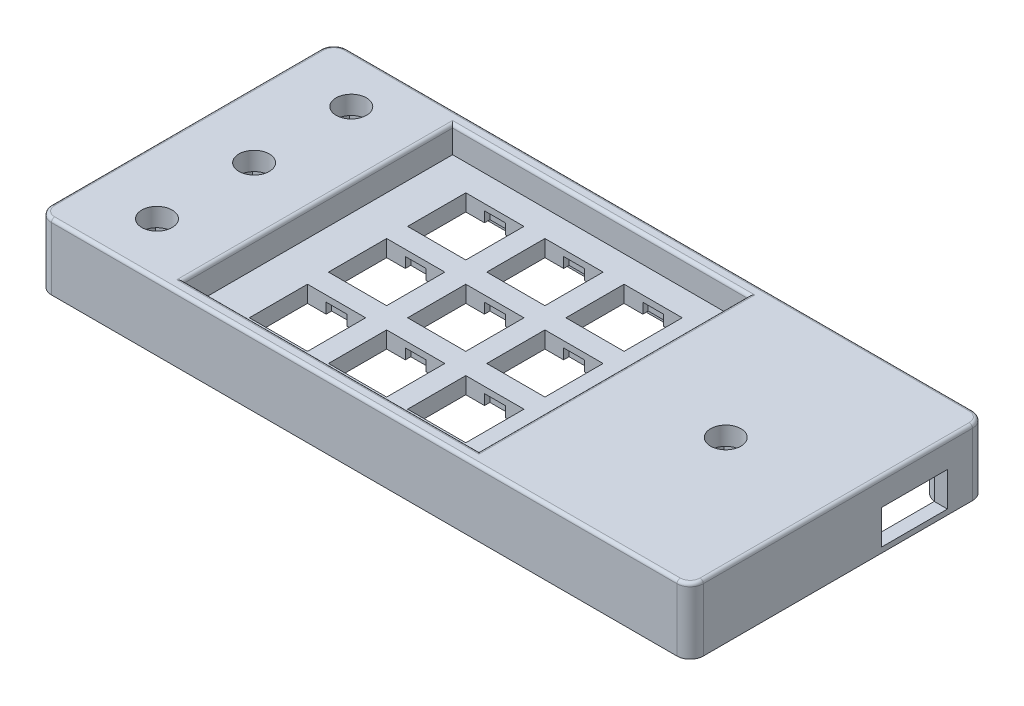
SolidWorks part; units mm, degrees
ref_plane "Front Plane" through (0, 0, 0) normal (0, 0, 1) x (1, 0, 0)
ref_plane "Top Plane" through (0, 0, 0) normal (0, 1, 0) x (1, 0, 0)
ref_plane "Right Plane" through (0, 0, 0) normal (1, 0, 0) x (0, 0, -1)
sketch "Sketch1" plane through (0, 0, 0) normal (0, 1, 0) x (1, 0, 0)
  line L1 (0, 0) -> (71.1479, 0)
  line L2 (0, 0) -> (0, 71.1479)
  line L3 (0, 71.1479) -> (71.1479, 71.1479)
  line L4 (71.1479, 0) -> (71.1479, 71.1479)
  dimension "D1" = 71.1479
  dimension "D2" = 71.1479
extrude "Boss-Extrude1" add sketch "Sketch1" along normal blind 4
sketch "Sketch2" plane through (0, 4, 0) normal (0, 1, 0) x (1, 0, 0)
  line L0 (9.525, 23.525) -> (23.525, 23.525)
  line L1 (9.525, 23.525) -> (9.525, 9.525)
  line L2 (9.525, 9.525) -> (23.525, 9.525)
  line L3 (23.525, 23.525) -> (23.525, 9.525)
  line L4 (0, 71.1479) -> (0, 0) construction
  line L5 (0, 0) -> (71.1479, 0) construction
  dimension "D1" = 9.525
  dimension "D2" = 9.525
  dimension "D3" = 14
extrude "Cut-Extrude1" cut sketch "Sketch2" against normal through all
sketch "Sketch3" plane through (0, 4, 0) normal (0, 1, 0) x (1, 0, 0)
  line L0 (14.0255, 23.525) -> (19.0245, 23.525)
  line L1 (14.0255, 23.525) -> (14.0255, 24.8321)
  line L2 (14.0255, 24.8321) -> (19.0245, 24.8321)
  line L3 (19.0245, 23.525) -> (19.0245, 24.8321)
  line L4 (9.525, 16.525) -> (23.525, 16.525) construction
  line L5 (9.525, 23.525) -> (9.525, 9.525) construction
  line L6 (23.525, 9.525) -> (23.525, 23.525) construction
  line L7 (23.525, 23.525) -> (9.525, 23.525) construction
  line L8 (14.0255, 9.525) -> (14.0255, 8.2179)
  line L9 (14.0255, 8.2179) -> (19.0245, 8.2179)
  line L10 (19.0245, 9.525) -> (19.0245, 8.2179)
  line L11 (14.0255, 9.525) -> (19.0245, 9.525)
  point P13 (16.525, 23.525)
  point P14 (16.525, 16.525)
  dimension "D1" = 4.999
  dimension "D2" = 1.3071
extrude "Cut-Extrude2" cut sketch "Sketch3" along normal blind 2.5001 from surface at -4 starting at face at (16.525, 0, -16.525)
pattern_linear "LPattern1" count 3 spacing 19.049 along (1, 0, 0) count 3 spacing 19.049 along (0, 0, -1) of "Cut-Extrude2", "Cut-Extrude1"
sketch "Sketch4" plane through (0, 0, 0) normal (0, 1, 0) x (1, 0, 0)
  line L0 (71.1479, 71.1479) -> (0, 71.1479) construction
  line L1 (0, 0) -> (-31.75, 0)
  line L2 (0, 0) -> (0, 71.1479)
  line L3 (0, 71.1479) -> (-31.75, 71.1479)
  line L4 (-31.75, 0) -> (-31.75, 71.1479)
  dimension "D1" = 31.75
extrude "Boss-Extrude2" add sketch "Sketch4" along normal blind 12.7 from offset 2.35 offset against normal yes
sketch "Sketch5" plane through (0, 10.35, 0) normal (0, 1, 0) x (1, 0, 0)
  line L0 (-31.75, 12.7) -> (0, 12.7) construction
  line L1 (-31.75, 71.1479) -> (-31.75, 0) construction
  line L2 (0, 0) -> (0, 71.1479) construction
  line L4 (-31.75, 0) -> (0, 0) construction
  circle A0 centre (-15.875, 12.7) radius 3.6576
  dimension "D1" = 7.3152
  dimension "D2" = 12.7
extrude "Cut-Extrude3" cut sketch "Sketch5" against normal blind 4.445
sketch "Sketch6" plane through (0, 10.35, 0) normal (0, 1, 0) x (1, 0, 0)
  line L0 (-22.86, 19.304) -> (-8.89, 19.304)
  line L1 (-22.86, 19.304) -> (-22.86, 6.096)
  line L2 (-22.86, 6.096) -> (-8.89, 6.096)
  line L3 (-8.89, 19.304) -> (-8.89, 6.096)
  line L4 (-31.75, 12.7) -> (0, 12.7) construction
  point P6 (-22.86, 12.7)
  point P10 (-15.875, 6.096)
  dimension "D1" = 13.97
  dimension "D2" = 13.208
extrude "Cut-Extrude4" cut sketch "Sketch6" along normal up to surface (8.255 mm away) from surface at -12.7 up to face at (-15.875, 5.905, -9.0424) starting at face at (-15.875, -2.35, -35.574)
sketch "Sketch7" plane through (0, -2.35, 0) normal (0, -1, 0) x (1, 0, 0)
  line L0 (-22.86, -9.2075) -> (-24.13, -9.2075)
  line L1 (-22.86, -9.2075) -> (-22.86, -16.1925)
  line L2 (-22.86, -16.1925) -> (-24.13, -16.1925)
  line L3 (-24.13, -9.2075) -> (-24.13, -16.1925)
  line L4 (-22.86, -6.096) -> (-22.86, -19.304) construction
  line L5 (-15.875, -6.096) -> (-15.875, -19.304) construction
  line L6 (-8.89, -6.096) -> (-22.86, -6.096) construction
  line L7 (-22.86, -19.304) -> (-8.89, -19.304) construction
  line L8 (-8.89, -9.2075) -> (-8.89, -16.1925)
  line L9 (-8.89, -16.1925) -> (-7.62, -16.1925)
  line L10 (-7.62, -9.2075) -> (-7.62, -16.1925)
  line L11 (-8.89, -9.2075) -> (-7.62, -9.2075)
  point P7 (-22.86, -12.7)
  point P8 (-22.86, -12.7)
  dimension "D1" = 6.985
  dimension "D2" = 1.27
extrude "Cut-Extrude5" cut sketch "Sketch7" against normal blind 3.175
pattern_linear "LPattern6" count 3 spacing 23.382 along (0, 0, -1) of "Cut-Extrude3", "Cut-Extrude4", "Cut-Extrude5"
sketch "Sketch9" plane through (0, 0, 0) normal (0, 1, 0) x (1, 0, 0)
  line L0 (71.1479, 0) -> (71.1479, 71.1479) construction
  line L1 (71.1479, 0) -> (125.144, 0)
  line L2 (71.1479, 0) -> (71.1479, 71.1479)
  line L3 (71.1479, 71.1479) -> (125.144, 71.1479)
  line L4 (125.144, 0) -> (125.144, 71.1479)
  line L5 (71.1479, 71.1479) -> (0, 71.1479) construction
  line L6 (71.1479, 35.574) -> (125.144, 35.574) construction
  line L7 (0, 0) -> (71.1479, 0) construction
  circle A0 centre (98.146, 35.574) radius 22.225 construction
  dimension "D1" = 44.45
extrude "Boss-Extrude3" add sketch "Sketch9" along normal up to surface (12.7 mm away) from surface at -2.35 up to face at (-15.875, 10.35, -55.8063) starting at face at (-15.875, -2.35, -59.4639)
sketch "Sketch10" plane through (0, 10.35, 0) normal (0, 1, 0) x (1, 0, 0)
  line L3 (71.1479, 35.574) -> (125.144, 35.574) construction
  line L5 (71.1479, 0) -> (71.1479, 71.1479) construction
  line L6 (125.144, 0) -> (125.144, 71.1479) construction
  circle A0 centre (98.146, 35.574) radius 3.6576
  dimension "D1" = 7.3152
extrude "Cut-Extrude6" cut sketch "Sketch10" against normal blind 4.445
sketch "Sketch11" plane through (0, 5.905, 0) normal (0, 1, 0) x (1, 0, 0)
  line L0 (91.161, 42.178) -> (105.131, 42.178)
  line L1 (91.161, 42.178) -> (91.161, 28.97)
  line L2 (91.161, 28.97) -> (105.131, 28.97)
  line L3 (105.131, 42.178) -> (105.131, 28.97)
  line L5 (71.1479, 35.574) -> (125.144, 35.574) construction
  point P6 (91.161, 35.574)
  point P12 (98.146, 35.574)
  point P13 (98.146, 28.97)
  dimension "D1" = 13.97
  dimension "D2" = 13.208
extrude "Cut-Extrude7" cut sketch "Sketch11" along normal up to surface (8.255 mm away) from surface at -8.255 up to face at (98.146, 5.905, -31.9164) starting at face at (98.146, -2.35, -35.574)
sketch "Sketch14" plane through (0, -2.35, 0) normal (0, -1, 0) x (1, 0, 0)
  line L0 (91.161, -32.0815) -> (89.891, -32.0815)
  line L1 (91.161, -32.0815) -> (91.161, -39.0665)
  line L2 (91.161, -39.0665) -> (89.891, -39.0665)
  line L3 (89.891, -32.0815) -> (89.891, -39.0665)
  line L5 (98.146, -28.97) -> (98.146, -42.178) construction
  line L8 (105.131, -32.0815) -> (105.131, -39.0665)
  line L9 (105.131, -39.0665) -> (106.401, -39.0665)
  line L10 (106.401, -32.0815) -> (106.401, -39.0665)
  line L11 (105.131, -32.0815) -> (106.401, -32.0815)
  line L13 (91.161, -42.178) -> (105.131, -42.178) construction
  line L14 (105.131, -28.97) -> (91.161, -28.97) construction
  line L15 (91.161, -28.97) -> (91.161, -42.178) construction
  point P8 (91.161, -35.574)
  point P11 (98.146, -42.178)
  point P14 (98.146, -28.97)
  point P21 (91.161, -35.574)
  dimension "D1" = 6.985
  dimension "D2" = 1.27
extrude "Cut-Extrude10" cut sketch "Sketch14" against normal blind 3.175
sketch "Sketch15" plane through (0, 4, 0) normal (0, 1, 0) x (1, 0, 0)
  line L0 (71.1479, 71.1479) -> (71.1479, 0) construction
  line L1 (0, 71.1479) -> (71.1479, 71.1479)
  line L2 (0, 71.1479) -> (0, 67.9729)
  line L3 (0, 67.9729) -> (71.1479, 67.9729)
  line L4 (71.1479, 71.1479) -> (71.1479, 67.9729)
  line L6 (0, 0) -> (71.1479, 0)
  line L7 (0, 0) -> (0, 3.175)
  line L8 (0, 3.175) -> (71.1479, 3.175)
  line L9 (71.1479, 0) -> (71.1479, 3.175)
  dimension "D1" = 3.175
extrude "Boss-Extrude4" add sketch "Sketch15" along normal up to surface (6.35 mm away) up to face at (-15.875, 10.35, -55.8063)
sketch "Sketch18" plane through (0, -2.35, 0) normal (0, -1, 0) x (1, 0, 0)
  line L0 (-28.575, -67.9729) -> (-28.575, -3.175)
  line L1 (-31.75, -71.1479) -> (125.144, -71.1479)
  line L2 (-31.75, -71.1479) -> (-31.75, 0)
  line L3 (-31.75, 0) -> (125.144, 0)
  line L4 (125.144, -71.1479) -> (125.144, 0)
  line L5 (-28.575, -3.175) -> (121.969, -3.175)
  line L6 (121.969, -67.9729) -> (121.969, -3.175)
  line L7 (-28.575, -67.9729) -> (121.969, -67.9729)
  dimension "D1" = 3.175
extrude "Boss-Extrude9" add sketch "Sketch18" against normal up to body from offset 3.175
fillet "Fillet1" radius 3.175 8 edges at (-31.75, 2.4125, -71.1479) (125.144, 2.4125, -71.1479) (125.144, 2.4125, 0) (-31.75, 2.4125, 0) (121.969, -3.9375, -67.9729) (-28.575, -3.9375, -67.9729) (-28.575, -3.9375, -3.175) (121.969, -3.9375, -3.175)
fillet "Fillet2" radius 0.7937 12 edges at (124.2141, 10.35, -0.9299) (46.697, 10.35, 0) (-30.8201, 10.35, -0.9299) (-31.75, 10.35, -35.574) (-30.8201, 10.35, -70.218) (46.697, 10.35, -71.1479) (124.2141, 10.35, -70.218) (35.574, 10.35, -67.9729) (0, 10.35, -35.574) (35.574, 10.35, -3.175) (71.1479, 10.35, -35.574) (125.144, 10.35, -35.574)
sketch "Sketch19" plane through (0, -2.35, 0) normal (0, -1, 0) x (1, 0, 0)
  line L0 (105.131, -42.178) -> (91.161, -42.178) construction
  line L1 (88.621, -45.099) -> (107.671, -45.099)
  line L2 (88.621, -45.099) -> (88.621, -26.049)
  line L3 (88.621, -26.049) -> (107.671, -26.049)
  line L4 (71.1479, -67.9729) -> (118.794, -67.9729)
  line L6 (71.1479, -67.9729) -> (118.794, -67.9729)
  line L7 (71.1479, -3.175) -> (71.1479, -67.9729)
  line L11 (71.1479, -3.175) -> (71.1479, -67.9729)
  line L12 (107.671, -45.099) -> (107.671, -26.049)
  line L13 (91.161, -39.0665) -> (91.161, -32.0815) construction
  line L19 (121.969, -64.7979) -> (121.969, -6.35)
  line L21 (121.969, -64.7979) -> (121.969, -6.35)
  line L22 (118.794, -3.175) -> (71.1479, -3.175)
  line L23 (118.794, -3.175) -> (71.1479, -3.175)
  arc A2 (118.794, -67.9729) -> (121.969, -64.7979) centre (118.794, -64.7979) ccw
  arc A6 (118.794, -67.9729) -> (121.969, -64.7979) centre (118.794, -64.7979) ccw
  arc A8 (121.969, -6.35) -> (118.794, -3.175) centre (118.794, -6.35) ccw
  arc A9 (121.969, -6.35) -> (118.794, -3.175) centre (118.794, -6.35) ccw
  point P14 (98.146, -42.178)
  point P15 (98.146, -45.099)
  point P18 (91.161, -35.574)
  point P19 (88.621, -35.574)
  dimension "D2" = 19.05
  dimension "D1" = 0
extrude "Cut-Extrude11" cut sketch "Sketch19" against normal up to surface (2.35 mm away) up to face at (35.574, 0, -16.525)
sketch "Sketch20" plane through (0, 0, 0) normal (0, -1, 0) x (1, 0, 0)
  line L0 (71.1479, -3.175) -> (71.1479, -67.9729) construction
  line L1 (71.1479, -3.175) -> (71.1479, -67.9729) construction
  line L3 (-25.4, -67.9729) -> (118.794, -67.9729) construction
  line L4 (121.969, -64.7979) -> (121.969, -6.35) construction
  line L5 (118.794, -3.175) -> (-25.4, -3.175) construction
  line L7 (72.7354, -67.9729) -> (118.794, -67.9729)
  line L8 (121.969, -64.7979) -> (121.969, -6.35)
  line L9 (118.794, -3.175) -> (72.7354, -3.175)
  line L10 (72.7354, -3.175) -> (72.7354, -67.9729)
  line L11 (88.621, -45.099) -> (107.671, -45.099) construction
  line L12 (107.671, -45.099) -> (107.671, -26.049) construction
  line L13 (107.671, -26.049) -> (88.621, -26.049) construction
  line L14 (88.621, -26.049) -> (88.621, -45.099) construction
  line L15 (88.621, -45.099) -> (107.671, -45.099)
  line L16 (107.671, -45.099) -> (107.671, -26.049)
  line L17 (107.671, -26.049) -> (88.621, -26.049)
  line L18 (88.621, -26.049) -> (88.621, -45.099)
  arc A2 (118.794, -67.9729) -> (121.969, -64.7979) centre (118.794, -64.7979) ccw construction
  arc A3 (121.969, -6.35) -> (118.794, -3.175) centre (118.794, -6.35) ccw construction
  arc A6 (118.794, -67.9729) -> (121.969, -64.7979) centre (118.794, -64.7979) ccw
  arc A7 (121.969, -6.35) -> (118.794, -3.175) centre (118.794, -6.35) ccw
  dimension "D1" = 3.175
extrude "Cut-Extrude13" cut sketch "Sketch20" against normal offset from surface (7.175 mm away) 3.175 up to face at (35.574, 10.35, -35.574)
sketch "Sketch21" plane through (0, -5.525, 0) normal (0, -1, 0) x (1, 0, 0)
  line L0 (121.969, 0) -> (-28.575, 0) construction
  line L1 (-31.75, -3.175) -> (-31.75, -67.9729) construction
  line L2 (-28.575, -71.1479) -> (121.969, -71.1479) construction
  line L3 (0, -3.175) -> (0, -67.9729) construction
  line L4 (72.7354, -3.175) -> (72.7354, -67.9729) construction
  line L5 (125.144, -67.9729) -> (125.144, -3.175) construction
  circle A0 centre (-27.7812, -3.9688) radius 3.9688
  circle A1 centre (-27.7812, -67.1792) radius 3.9688
  circle A2 centre (121.1752, -67.1792) radius 3.9687
  circle A3 centre (121.1752, -3.9688) radius 3.9687
  circle A4 centre (0, -3.9688) radius 3.9688
  circle A5 centre (72.7354, -67.1792) radius 3.9688
  dimension "D1" = 7.9375
extrude "Boss-Extrude10" add sketch "Sketch21" against normal up to body
sketch "Sketch22" plane through (0, -5.525, 0) normal (0, -1, 0) x (1, 0, 0)
  circle A0 centre (-27.7812, -3.9688) radius 2.54
  circle A1 centre (0, -3.9688) radius 2.54
  circle A2 centre (72.7354, -67.1792) radius 2.54
  circle A3 centre (-27.7812, -67.1792) radius 2.54
  circle A4 centre (121.1752, -67.1792) radius 2.54
  circle A5 centre (121.1752, -3.9688) radius 2.54
  dimension "D1" = 5.08
extrude "Cut-Extrude14" cut sketch "Sketch22" against normal blind 8.001
sketch "Sketch24" plane through (0, 7.175, 0) normal (0, -1, 0) x (1, 0, 0)
  line L0 (121.969, -63.2906) -> (121.969, -7.8573) construction
  line L1 (86.409, -45.099) -> (121.969, -45.099) construction
  line L2 (86.409, -45.099) -> (86.409, -62.879) construction
  line L3 (86.409, -62.879) -> (121.969, -62.879) construction
  line L4 (121.969, -45.099) -> (121.969, -62.879) construction
  line L5 (88.621, -45.099) -> (107.671, -45.099) construction
  line L7 (118.794, -50.814) -> (121.969, -50.814)
  line L8 (118.794, -50.814) -> (118.794, -57.164)
  line L9 (118.794, -57.164) -> (121.969, -57.164)
  line L10 (121.969, -50.814) -> (121.969, -57.164)
  point P13 (121.969, -53.989)
  point P14 (121.969, -53.989)
  dimension "D1" = 17.78
  dimension "D2" = 35.56
  dimension "D3" = 3.175
  dimension "D4" = 6.35
extrude "Boss-Extrude11" add sketch "Sketch24" along normal blind 3.175
sketch "Sketch25" plane through (0, 7.175, 0) normal (0, -1, 0) x (1, 0, 0)
  line L0 (118.794, -50.814) -> (118.794, -57.164) construction
  line L1 (88.6315, -50.814) -> (94.9815, -50.814)
  line L2 (88.6315, -50.814) -> (88.6315, -57.164)
  line L3 (88.6315, -57.164) -> (94.9815, -57.164)
  line L4 (94.9815, -50.814) -> (94.9815, -57.164)
  line L5 (121.969, -45.099) -> (121.969, -62.879) construction
  point P6 (118.794, -53.989)
  point P7 (94.9815, -53.989)
  dimension "D1" = 6.35
  dimension "D2" = 26.9875
extrude "Boss-Extrude12" add sketch "Sketch25" along normal up to surface (3.175 mm away) up to face at (120.3815, 4, -53.989)
sketch "Sketch27" plane through (0, 7.175, 0) normal (0, -1, 0) x (1, 0, 0)
  line L0 (86.409, -62.879) -> (121.969, -62.879) construction
  line L1 (104.496, -62.879) -> (107.671, -62.879)
  line L2 (104.496, -62.879) -> (104.496, -67.9729)
  line L3 (104.496, -67.9729) -> (107.671, -67.9729)
  line L4 (107.671, -62.879) -> (107.671, -67.9729)
  line L5 (76.624, -67.9729) -> (117.2867, -67.9729) construction
  line L6 (107.671, -45.099) -> (107.671, -26.049) construction
  dimension "D1" = 3.175
extrude "Boss-Extrude13" add sketch "Sketch27" along normal blind 8.1915
sketch "Sketch26" plane through (0, 4, 0) normal (0, -1, 0) x (1, 0, 0)
  line L1 (104.496, -46.6865) -> (107.671, -46.6865)
  line L2 (104.496, -46.6865) -> (104.496, -45.099)
  line L3 (104.496, -45.099) -> (107.671, -45.099)
  line L4 (107.671, -46.6865) -> (107.671, -45.099)
  line L5 (107.671, -45.099) -> (107.671, -26.049) construction
  line L6 (86.409, -45.099) -> (121.969, -45.099) construction
  line L8 (104.496, -62.879) -> (107.671, -62.879)
  line L9 (104.496, -62.879) -> (104.496, -61.2915)
  line L10 (104.496, -61.2915) -> (107.671, -61.2915)
  line L11 (107.671, -62.879) -> (107.671, -61.2915)
  dimension "D1" = 3.175
  dimension "D2" = 1.5875
extrude "Boss-Extrude14" add sketch "Sketch26" along normal blind 1.5875 from offset 1.7145
sketch "Sketch28" plane through (121.969, 0, 0) normal (-1, 0, 0) x (0, 0, 1)
  line L0 (-57.164, 4) -> (-50.814, 4) construction
  line L1 (-61.9265, 4) -> (-46.0515, 4)
  line L2 (-61.9265, 4) -> (-61.9265, -4.255)
  line L3 (-61.9265, -4.255) -> (-46.0515, -4.255)
  line L4 (-46.0515, 4) -> (-46.0515, -4.255)
  point P6 (-53.989, 4)
  point P7 (-53.989, 4)
  dimension "D1" = 15.875
  dimension "D2" = 8.255
extrude "Cut-Extrude15" cut sketch "Sketch28" against normal through all
sketch "Sketch29" plane through (0, -5.525, 0) normal (0, -1, 0) x (1, 0, 0)
  line L0 (-31.75, -3.175) -> (-31.75, -67.9729) construction
  line L1 (-22.86, -6.096) -> (-8.89, -6.096)
  line L2 (-22.86, -6.096) -> (-22.86, -19.304)
  line L3 (-22.86, -19.304) -> (-8.89, -19.304)
  line L4 (-8.89, -6.096) -> (-8.89, -19.304)
  line L5 (-22.86, -29.478) -> (-8.89, -29.478)
  line L6 (-22.86, -29.478) -> (-22.86, -42.686)
  line L7 (-22.86, -42.686) -> (-8.89, -42.686)
  line L8 (-8.89, -29.478) -> (-8.89, -42.686)
  line L9 (-22.86, -52.8599) -> (-8.89, -52.8599)
  line L10 (-22.86, -52.8599) -> (-22.86, -66.0679)
  line L11 (-22.86, -66.0679) -> (-8.89, -66.0679)
  line L12 (-8.89, -52.8599) -> (-8.89, -66.0679)
  line L13 (91.161, -28.97) -> (105.131, -28.97)
  line L14 (91.161, -28.97) -> (91.161, -42.178)
  line L15 (91.161, -42.178) -> (105.131, -42.178)
  line L16 (105.131, -28.97) -> (105.131, -42.178)
  line L17 (121.969, 0) -> (-28.575, 0) construction
  dimension "D1" = 13.208
  dimension "D2" = 13.97
  dimension "D3" = 23.382
  dimension "D4" = 46.7639
  dimension "D5" = 100.051
  dimension "D6" = 22.874
  dimension "D7" = 8.89
  dimension "D8" = 6.096
equation "\"D2@Sketch2\"=\"D1@Sketch2\""
equation "\"D1@Sketch1\"=\"D2@Sketch1\""
